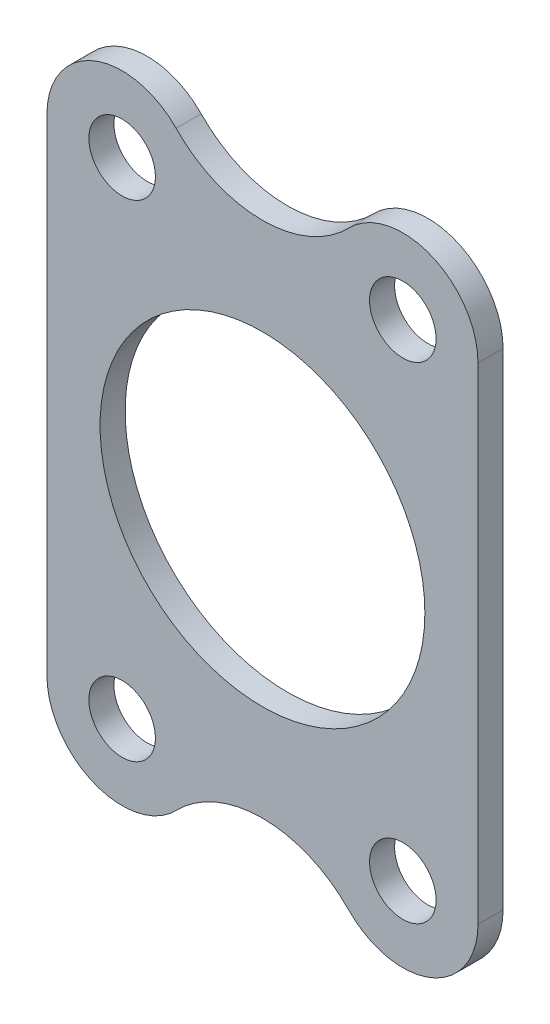
SolidWorks part; units mm, degrees
material "AISI 304"
ref_plane "Front Plane" through (0, 0, 0) normal (0, 0, 1) x (1, 0, 0)
ref_plane "Top Plane" through (0, 0, 0) normal (0, 1, 0) x (1, 0, 0)
ref_plane "Right Plane" through (0, 0, 0) normal (1, 0, 0) x (0, 0, -1)
sketch "Sketch1" plane through (0, 0, 16.51) normal (0, 0, 1) x (1, 0, 0)
  line L4 (13.6525, -15.3979) -> (13.6525, 15.3979)
  line L5 (13.6525, -15.3979) -> (13.6525, 15.3979)
  line L6 (-13.6525, 15.3979) -> (-13.6525, -15.3979)
  line L7 (-13.6525, 15.3979) -> (-13.6525, -15.3979)
  circle A1 centre (8.89, -15.3979) radius 2.1082
  circle A2 centre (8.89, -15.3979) radius 2.1082
  circle A3 centre (-8.89, -15.3979) radius 2.1082
  circle A4 centre (-8.89, -15.3979) radius 2.1082
  circle A5 centre (0, 0) radius 10.287
  circle A6 centre (0, 0) radius 10.287
  circle A7 centre (8.89, 15.3979) radius 2.1082
  circle A8 centre (8.89, 15.3979) radius 2.1082
  circle A9 centre (-8.89, 15.3979) radius 2.1082
  circle A10 centre (-8.89, 15.3979) radius 2.1082
  arc A14 (-5.4708, 18.7131) -> (-13.6525, 15.3979) centre (-8.89, 15.3979) ccw
  arc A15 (-5.4708, 18.7131) -> (5.4708, 18.7131) centre (0, 24.0173) ccw
  arc A16 (13.6525, 15.3979) -> (5.4708, 18.7131) centre (8.89, 15.3979) ccw
  arc A18 (5.4708, -18.7131) -> (13.6525, -15.3979) centre (8.89, -15.3979) ccw
  arc A19 (5.4708, -18.7131) -> (-5.4708, -18.7131) centre (0, -24.0173) ccw
  arc A20 (-13.6525, -15.3979) -> (-5.4708, -18.7131) centre (-8.89, -15.3979) ccw
  arc A22 (-5.4708, 18.7131) -> (-13.6525, 15.3979) centre (-8.89, 15.3979) ccw
  arc A23 (-5.4708, 18.7131) -> (5.4708, 18.7131) centre (0, 24.0173) ccw
  arc A24 (13.6525, 15.3979) -> (5.4708, 18.7131) centre (8.89, 15.3979) ccw
  arc A26 (5.4708, -18.7131) -> (13.6525, -15.3979) centre (8.89, -15.3979) ccw
  arc A27 (5.4708, -18.7131) -> (-5.4708, -18.7131) centre (0, -24.0173) ccw
  arc A28 (-13.6525, -15.3979) -> (-5.4708, -18.7131) centre (-8.89, -15.3979) ccw
  dimension "D1" = 0
  dimension "D2" = 0
  dimension "D3" = 0
  dimension "D4" = 0
  dimension "D5" = 0
  dimension "D6" = 0
extrude "Boss-Extrude1" add sketch "Sketch1" along normal blind 1.5875
